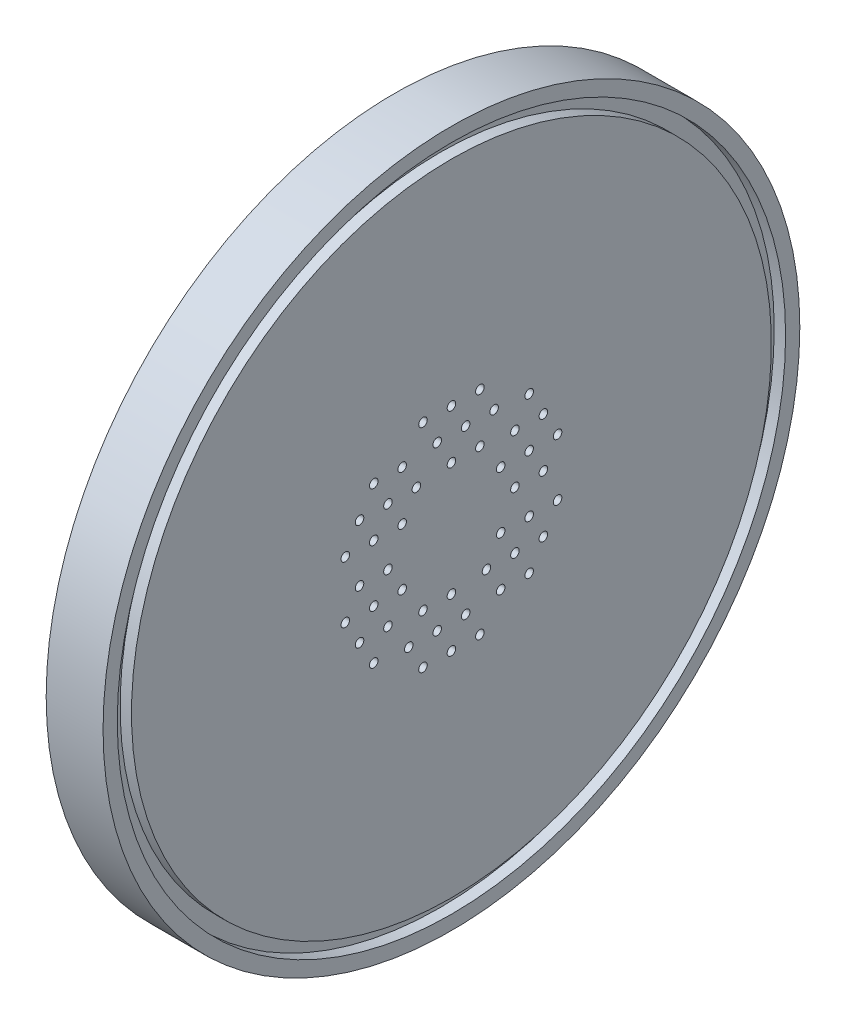
SolidWorks part; units mm, degrees
ref_plane "Front Plane" through (0, 0, 0) normal (0, 0, 1) x (1, 0, 0)
ref_plane "Top Plane" through (0, 0, 0) normal (0, 1, 0) x (1, 0, 0)
ref_plane "Right Plane" through (0, 0, 0) normal (1, 0, 0) x (0, 0, -1)
sketch "Sketch1" plane through (0, 0, 0) normal (0, 0, 1) x (1, 0, 0)
  line L0 (0, 0) -> (0, 48.26)
  line L1 (-2.54, 50.8) -> (-6.35, 50.8)
  line L2 (-6.35, 50.8) -> (-6.35, 76.2)
  line L3 (-6.35, 76.2) -> (3.81, 76.2)
  line L4 (3.81, 76.2) -> (3.81, 0)
  line L5 (3.81, 0) -> (0, 0)
  line L6 (-6.35, 50.8) -> (-6.35, 0) construction
  line L7 (-6.35, 0) -> (0, 0) construction
  arc A0 (0, 48.26) -> (-2.54, 50.8) centre (-2.54, 48.26) ccw
  dimension "Injector Plate Edge Curve" = 2.54
  dimension "Injector Plate Main Thickness" = 3.81
  dimension "Comp" = 152.4
  dimension "Injector Plate Boundry" = 25.4
  dimension "Injector Plate Manifold Height" = 6.35
revolve "Revolve1" add sketch "Sketch1" angle 360 about L7
sketch "Sketch2" plane through (3.81, 0, 0) normal (1, 0, 0) x (0, 0, -1)
  line L0 (0, 10.16) -> (5.08, 10.16) construction
  line L37 (5.08, 10.16) -> (2.54, 14.5594) construction
  line L38 (0, 10.16) -> (-2.54, 14.5594) construction
  line L39 (2.54, 14.5594) -> (0, 10.16) construction
  line L40 (-2.54, 14.5594) -> (2.54, 14.5594) construction
  line L41 (2.54, 14.5594) -> (7.62, 14.5594) construction
  line L42 (7.62, 14.5594) -> (5.08, 10.16) construction
  line L43 (2.54, 14.5594) -> (5.08, 18.9588) construction
  line L44 (5.08, 18.9588) -> (7.62, 14.5594) construction
  line L45 (-2.54, 14.5594) -> (0, 18.9588) construction
  line L46 (0, 18.9588) -> (2.54, 14.5594) construction
  line L47 (0, 18.9588) -> (5.08, 18.9588) construction
  line L48 (-2.54, 14.5594) -> (-5.08, 18.9588) construction
  line L49 (-5.08, 18.9588) -> (0, 18.9588) construction
  circle A3 centre (0, 10.16) radius 0.762
  circle A7 centre (-2.54, 14.5594) radius 0.762
  circle A8 centre (5.08, 10.16) radius 0.762
  circle A9 centre (-5.08, 18.9588) radius 0.762
  circle A10 centre (0, 18.9588) radius 0.762
  circle A11 centre (5.08, 18.9588) radius 0.762
  circle A12 centre (7.62, 14.5594) radius 0.762
  circle A13 centre (2.54, 14.5594) radius 0.762
  dimension "Injector Plate Holes Diameter" = 1.524
  dimension "Distance Between Holes" = 5.08
  dimension "1st Hole Distance from Center" = 10.16
extrude "Cut-Extrude1" cut sketch "Sketch2" against normal through all
chamfer "Chamfer1" distance 0.508 8 edges at (0, 10.922, 0) (0, 10.922, -5.08) (0, 15.3214, -7.62) (0, 15.3214, -2.54) (0, 15.3214, 2.54) (0, 19.7208, 5.08) (0, 19.7208, 0) (0, 19.7208, -5.08)
pattern_circular "CirPattern1" count 6 over 360 about axis through (0, 0, 0) along (1, 0, 0) of "Cut-Extrude1", "Chamfer1"
sketch "Sketch3" plane through (3.81, 0, 0) normal (1, 0, 0) x (0, 0, -1)
  line L0 (-66.802, 0) -> (0, 0) construction
  circle A0 centre (-66.802, 0) radius 3.175
  dimension "Screw Hole Diameter" = 6.35
  dimension "Injector Plate Screw Hole Distance" = 66.802
extrude "Cut-Extrude2" cut sketch "Sketch3" against normal through all
pattern_circular "CirPattern2" count 8 over 360 about axis through (0, 0, 0) along (1, 0, 0) of "Cut-Extrude2"
sketch "Sketch4" plane through (0, 0, 0) normal (0, 0, 1) x (1, 0, 0)
  line L0 (3.81, -76.2) -> (3.81, 76.2) construction
  line L1 (3.81, 59.69) -> (1.778, 59.69)
  line L2 (3.81, 59.69) -> (3.81, 57.15)
  line L3 (3.81, 57.15) -> (1.778, 57.15)
  line L4 (1.778, 59.69) -> (1.778, 57.15)
  line L5 (-6.35, 76.2) -> (-6.35, -76.2) construction
  line L11 (0, 0) -> (-6.35, 0) construction
  dimension "O-Ring Depth" = 2.032
  dimension "O-Ring Width" = 2.54
  dimension "O-Ring Radius" = 57.15
revolve "Cut-Revolve1" cut sketch "Sketch4" angle 360 about L11
sketch "Sketch5" plane through (0, 0, 0) normal (1, 0, 0) x (0, 0, -1)
  circle A0 centre (0, 0) radius 62.23
  circle A1 centre (0, 0) radius 76.2
extrude "Cut-Extrude3" cut sketch "Sketch5" against normal through all both and the other way through all
sketch "Sketch6" plane through (0, 0, 0) normal (-1, 0, 0) x (0, 0, 1)
  circle A0 centre (0, 0) radius 25.4
  circle A1 centre (0, 0) radius 31.75
extrude "Boss-Extrude1" add sketch "Sketch6" along normal blind 6.35
sketch "Sketch7" plane through (-6.35, 0, 0) normal (-1, 0, 0) x (0, 0, 1)
  line L2 (8.3058, -30.6443) -> (8.3058, 30.6443)
  line L4 (-8.3058, -30.6443) -> (-8.3058, 30.6443)
  line L5 (8.3058, -30.6443) -> (-8.3058, 30.6443) construction
  line L6 (8.3058, 30.6443) -> (-8.3058, -30.6443) construction
  circle A0 centre (0, 0) radius 31.75 construction
  circle A1 centre (0, 0) radius 31.75 construction
  arc A2 (-8.3058, -30.6443) -> (8.3058, -30.6443) centre (0, 0) ccw
  arc A3 (8.3058, 30.6443) -> (-8.3058, 30.6443) centre (0, 0) ccw
  point P0 (0, 0)
  dimension "D1" = 16.6116
extrude "Cut-Extrude4" cut sketch "Sketch7" against normal blind 6.35
pattern_circular "CirPattern3" count 6 over 360 about axis through (0, 0, 0) along (1, 0, 0) of "Cut-Extrude4"
